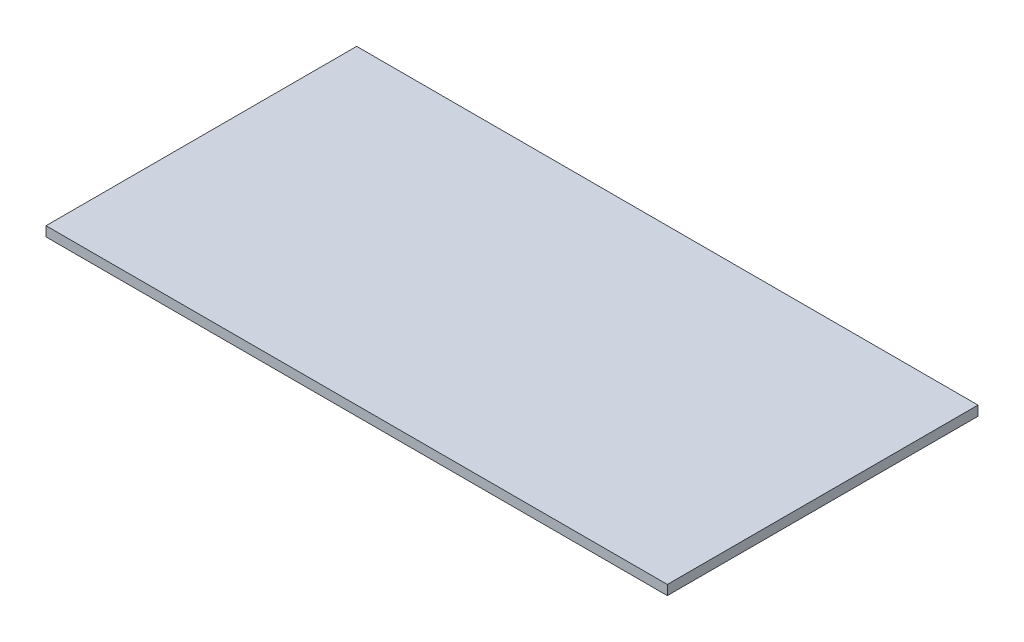
SolidWorks part; units mm, degrees
ref_plane "Front Plane" through (0, 0, 0) normal (0, 0, 1) x (1, 0, 0)
ref_plane "Top Plane" through (0, 0, 0) normal (0, 1, 0) x (1, 0, 0)
ref_plane "Right Plane" through (0, 0, 0) normal (1, 0, 0) x (0, 0, -1)
sketch "Sketch1" plane through (0, 0, 0) normal (0, 1, 0) x (1, 0, 0)
  line L1 (-59.1289, 123.9995) -> (245.6711, 123.9995)
  line L2 (-59.1289, 123.9995) -> (-59.1289, -28.4005)
  line L3 (-59.1289, -28.4005) -> (245.6711, -28.4005)
  line L4 (245.6711, 123.9995) -> (245.6711, -28.4005)
  dimension "D1" = 304.8
  dimension "D2" = 152.4
extrude "Boss-Extrude2" add sketch "Sketch1" along normal blind 4.7625
